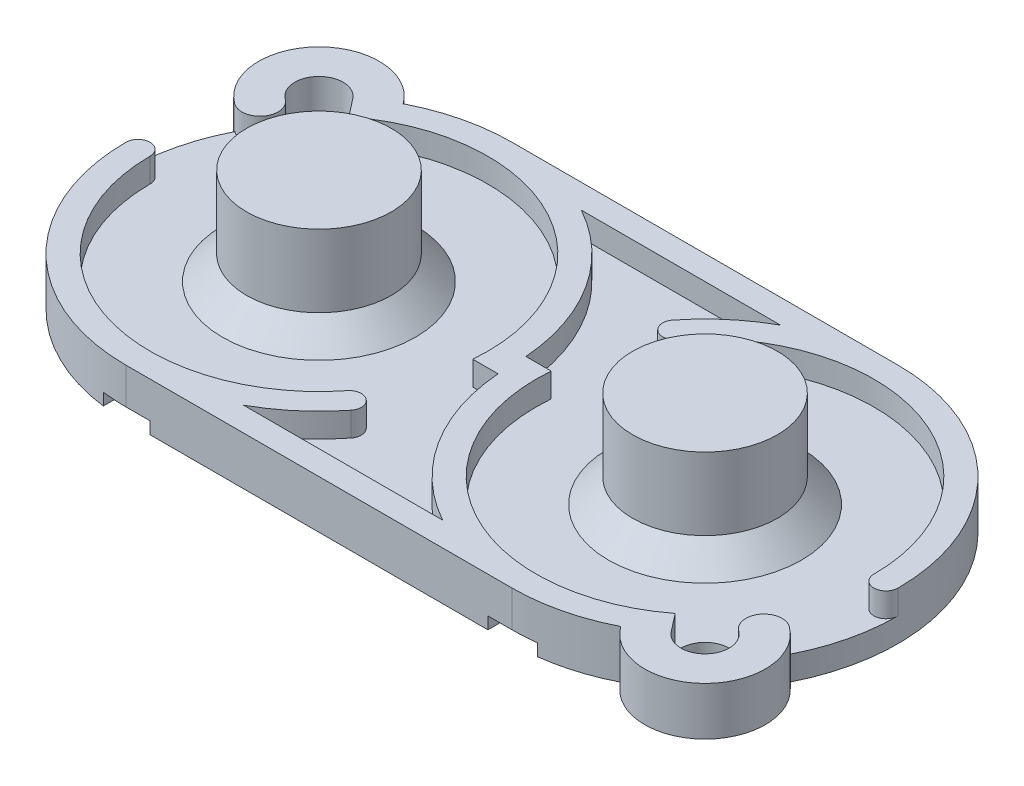
SolidWorks part; units mm, degrees
material "Silicon"
ref_plane "Front Plane" through (0, 0, 0) normal (0, 0, 1) x (1, 0, 0)
ref_plane "Top Plane" through (0, 0, 0) normal (0, 1, 0) x (1, 0, 0)
ref_plane "Right Plane" through (0, 0, 0) normal (1, 0, 0) x (0, 0, -1)
sketch "Sketch1" plane through (0, 0, 0) normal (0, 1, 0) x (1, 0, 0)
  line L0 (0, 8) -> (16, 8)
  line L1 (0, -8) -> (16, -8)
  line L2 (0, 0) -> (16, 0) construction
  line L3 (-5.6569, 5.6569) -> (0, 0) construction
  line L5 (16, 0) -> (21.6569, -5.6569) construction
  arc A0 (0, 8) -> (-3.6346, 7.1267) centre (0, 0) ccw
  arc A1 (16, -8) -> (19.6346, -7.1267) centre (16, 0) ccw
  arc A2 (-3.6346, 7.1267) -> (-7.1267, 3.6346) centre (-5.6569, 5.6569) ccw
  circle A3 centre (-5.6569, 5.6569) radius 1
  circle A4 centre (21.6569, -5.6569) radius 1
  arc A5 (19.6346, -7.1267) -> (23.1267, -3.6346) centre (21.6569, -5.6569) ccw
  arc A6 (23.1267, -3.6346) -> (16, 8) centre (16, 0) ccw
  arc A7 (-7.1267, 3.6346) -> (0, -8) centre (0, 0) ccw
  dimension "D1" = 16
  dimension "D2" = 16
  dimension "D3" = 45
  dimension "D4" = 5
  dimension "D5" = 2
  dimension "D9" = 5
  dimension "D10" = 2
  dimension "D6" = 8
  dimension "D7" = 8
  dimension "D8" = 45
extrude "Base Extrude" add sketch "Sketch1" along normal blind 1
sketch "Sketch4" plane through (0, 1, 0) normal (0, 1, 0) x (1, 0, 0)
  line L0 (-8, 0) -> (8, 0) construction
  line L1 (-4.2922, 5.5296) -> (-4.8669, 6.27)
  line L2 (0, -8) -> (16, -8)
  line L3 (16, 8) -> (0, 8)
  line L4 (6.9742, -0.6) -> (8.0225, -0.6)
  line L6 (8, 0) -> (5.5, -4.3301) construction
  line L16 (0, -8) -> (16, -8) construction
  arc A1 (-7.1267, 3.6346) -> (-6.2448, 4.8479) centre (-6.6857, 4.2413) ccw
  circle A2 centre (-5.6569, 5.6569) radius 1 construction
  arc A3 (-7, 0) -> (5.5, -4.3301) centre (0, 0) ccw
  arc A4 (-8, 0) -> (-7, 0) centre (-7.5, 0) cw
  arc A6 (0, -8) -> (6.2857, -4.9487) centre (0, 0) ccw
  arc A7 (6.9742, -0.6) -> (-4.2922, 5.5296) centre (0, 0) ccw
  arc A8 (0, 8) -> (-3.6346, 7.1267) centre (0, 0) ccw
  arc A9 (-3.6346, 7.1267) -> (-7.1267, 3.6346) centre (-5.6569, 5.6569) ccw
  arc A10 (-7.1267, 3.6346) -> (0, -8) centre (0, 0) ccw
  arc A11 (16, -8) -> (19.6346, -7.1267) centre (16, 0) ccw
  arc A12 (19.6346, -7.1267) -> (23.1267, -3.6346) centre (21.6569, -5.6569) ccw
  arc A13 (23.1267, -3.6346) -> (16, 8) centre (16, 0) ccw
  arc A14 (0, 8) -> (-3.6346, 7.1267) centre (0, 0) ccw
  arc A15 (-3.6346, 7.1267) -> (-7.1267, 3.6346) centre (-5.6569, 5.6569) ccw
  arc A16 (-8, 0) -> (0, -8) centre (0, 0) ccw
  arc A17 (-4.8669, 6.27) -> (-6.2448, 4.8479) centre (-5.6569, 5.6569) ccw
  arc A20 (5.5, -4.3301) -> (6.2857, -4.9487) centre (5.8929, -4.6394) cw
  arc A21 (8, 0) -> (0, 8) centre (0, 0) ccw
  arc A22 (8, 0) -> (8.0225, -0.6) centre (16, 0) ccw
  dimension "D3" = 5
  dimension "D4" = 0.6
  dimension "D2" = 1
  dimension "D1" = 0
extrude "Boss-Extrude7" add sketch "Sketch4" along normal blind 1
sketch "Sketch8" plane through (0, 0, 0) normal (0, 0, 1) x (1, 0, 0)
  line L0 (8, 3.5929) -> (8, -2.1107) construction
  line L1 (8, 2) -> (8, 1) construction
pattern_circular "CirPattern1" count 2 over 360 about axis through (8, 0, 0) along (0, 1, 0) of "Boss-Extrude7"
sketch "Sketch9" plane through (0, 1, 0) normal (0, 1, 0) x (1, 0, 0)
  line L0 (12.127, 7) -> (3.873, 7)
  line L1 (3.873, -7) -> (12.127, -7)
  line L2 (0, 8) -> (16, 8)
  line L3 (16, -8) -> (0, -8)
  arc A0 (24, 0) -> (9.7143, 4.9487) centre (16, 0) ccw construction
  arc A1 (7.9775, 0.6) -> (-3.6346, 7.1267) centre (0, 0) ccw construction
  arc A2 (-8, 0) -> (6.2857, -4.9487) centre (0, 0) ccw construction
  arc A3 (8.0225, -0.6) -> (16, -8) centre (16, 0) ccw construction
  arc A4 (0, -8) -> (6.2857, -4.9487) centre (0, 0) ccw construction
  arc A5 (7.9775, 0.6) -> (0, 8) centre (0, 0) ccw construction
  arc A6 (16, 8) -> (9.7143, 4.9487) centre (16, 0) ccw construction
  arc A7 (12.127, -7) -> (16, -8) centre (16, 0) ccw
  arc A8 (0, -8) -> (3.873, -7) centre (0, 0) ccw
  arc A9 (3.873, 7) -> (0, 8) centre (0, 0) ccw
  arc A10 (16, 8) -> (12.127, 7) centre (16, 0) ccw
  dimension "D1" = 1
  dimension "D2" = 1
extrude "Boss-Extrude8" add sketch "Sketch9" along normal blind 1
sketch "Sketch10" plane through (0, 1, 0) normal (0, 1, 0) x (1, 0, 0)
  arc A0 (23, 0) -> (10.5, 4.3301) centre (16, 0) ccw construction
  arc A1 (23, 0) -> (10.5, 4.3301) centre (16, 0) ccw construction
  circle A2 centre (16, 0) radius 3
  circle A3 centre (0, 0) radius 3
  dimension "D1" = 6
extrude "Boss-Extrude9" add sketch "Sketch10" along normal blind 4
chamfer "Chamfer1" distance 1 angle 45 2 edges at (16, 1, 3) (0, 1, 3)
sketch "Sketch12" plane through (0, 0, 0) normal (0, 0, 1) x (1, 0, 0)
  line L0 (0, 3.203) -> (0, -1.7137) construction
  line L3 (0, 1.75) -> (2.5, 1.75)
  line L4 (2.5, 1.75) -> (3.5, 0.5)
  line L5 (3.5, 0.5) -> (3.5, 0)
  line L6 (16, 0) -> (0, 0) construction
  line L7 (3.5, 0) -> (0, 0)
  line L8 (0, 0) -> (0, 1.75)
  dimension "D1" = 3.5
  dimension "D2" = 2.5
  dimension "D3" = 1.75
  dimension "D4" = 0.5
revolve "Back Cavity" cut sketch "Sketch12" angle 360 about L0
ref_plane "Plane2" through (8, 0, 0) normal (1, 0, 0) x (0, 0, -1)
mirror "Mirror1" about plane through (8, 0, 0) normal (1, 0, 0) of "Back Cavity"
sketch "Sketch13" plane through (0, 0, 0) normal (0, -1, 0) x (1, 0, 0)
  line L0 (3.3541, 1) -> (12.6459, 1)
  line L1 (3.3541, -1) -> (12.6459, -1)
  line L3 (-1, 3.3541) -> (-1, 7.9373)
  line L4 (1, 3.3541) -> (1, 8)
  line L5 (0, 8) -> (16, 8) construction
  line L6 (16, -8) -> (0, -8) construction
  line L7 (16, -8) -> (15, -8)
  line L8 (0, 8) -> (1, 8)
  line L9 (-1, -3.3541) -> (-1, -7.9373)
  line L10 (1, -3.3541) -> (1, -8)
  line L11 (15, -3.3541) -> (15, -8)
  line L12 (17, -3.3541) -> (17, -7.9373)
  line L13 (15, 3.3541) -> (15, 8)
  line L14 (17, 7.9373) -> (17, 3.3541)
  line L15 (15, 8) -> (16, 8)
  line L16 (1, -8) -> (0, -8)
  circle A0 centre (0, 0) radius 3.5 construction
  circle A1 centre (16, 0) radius 3.5 construction
  circle A2 centre (0, 0) radius 3.5 construction
  arc A3 (0, 8) -> (-7.1267, -3.6346) centre (0, 0) ccw construction
  arc A4 (16, -8) -> (23.1267, 3.6346) centre (16, 0) ccw construction
  arc A5 (-3.6346, -7.1267) -> (0, -8) centre (0, 0) ccw construction
  arc A6 (19.6346, 7.1267) -> (16, 8) centre (16, 0) ccw construction
  circle A7 centre (16, 0) radius 3.5 construction
  arc A8 (16, -8) -> (17, -7.9373) centre (16, 0) ccw
  arc A9 (-1, -7.9373) -> (0, -8) centre (0, 0) ccw
  arc A10 (0, 8) -> (-1, 7.9373) centre (0, 0) ccw
  arc A11 (17, 7.9373) -> (16, 8) centre (16, 0) ccw
  arc A12 (17, 3.3541) -> (15, 3.3541) centre (16, 0) ccw
  arc A13 (1, 3.3541) -> (-1, 3.3541) centre (0, 0) ccw
  arc A14 (15, -3.3541) -> (17, -3.3541) centre (16, 0) ccw
  arc A15 (12.6459, 1) -> (12.6459, -1) centre (16, 0) ccw
  arc A16 (3.3541, -1) -> (3.3541, 1) centre (0, 0) ccw
  arc A17 (-1, -3.3541) -> (1, -3.3541) centre (0, 0) ccw
  dimension "D1" = 2
  dimension "D2" = 2
  dimension "D3" = 2
extrude "Cut-Extrude1" cut sketch "Sketch13" against normal blind 0.5
sketch "Sketch14" plane through (0, 1.75, 0) normal (0, -1, 0) x (1, 0, 0)
  circle A1 centre (0, 0) radius 2.5
  circle A2 centre (0, 0) radius 2.5
  dimension "D1" = 0
extrude "Boss-Extrude10" add sketch "Sketch14" along normal blind 0.5
mirror "Mirror2" about plane through (8, 0, 0) normal (1, 0, 0) of "Boss-Extrude10"
